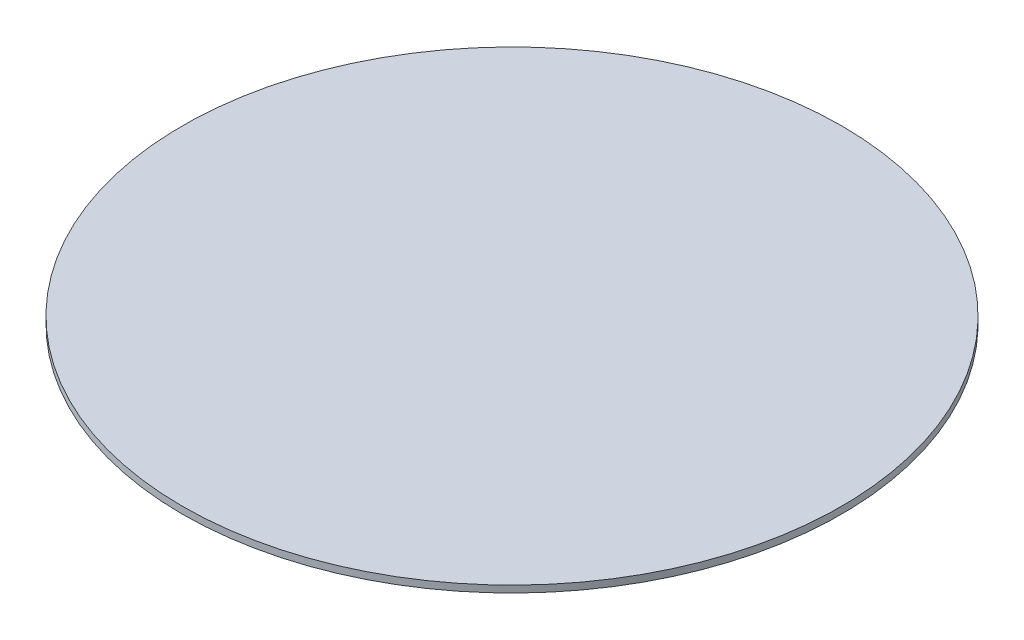
SolidWorks part; units mm, degrees
ref_plane "Front Plane" through (0, 0, 0) normal (0, 0, 1) x (1, 0, 0)
ref_plane "Top Plane" through (0, 0, 0) normal (0, 1, 0) x (1, 0, 0)
ref_plane "Right Plane" through (0, 0, 0) normal (1, 0, 0) x (0, 0, -1)
sketch "Sketch1" plane through (0, 0, 0) normal (0, 1, 0) x (1, 0, 0)
  circle A0 centre (0, 0) radius 95.25
  dimension "D1" = 190.5
extrude "Boss-Extrude1" add sketch "Sketch1" along normal blind 1.9844
